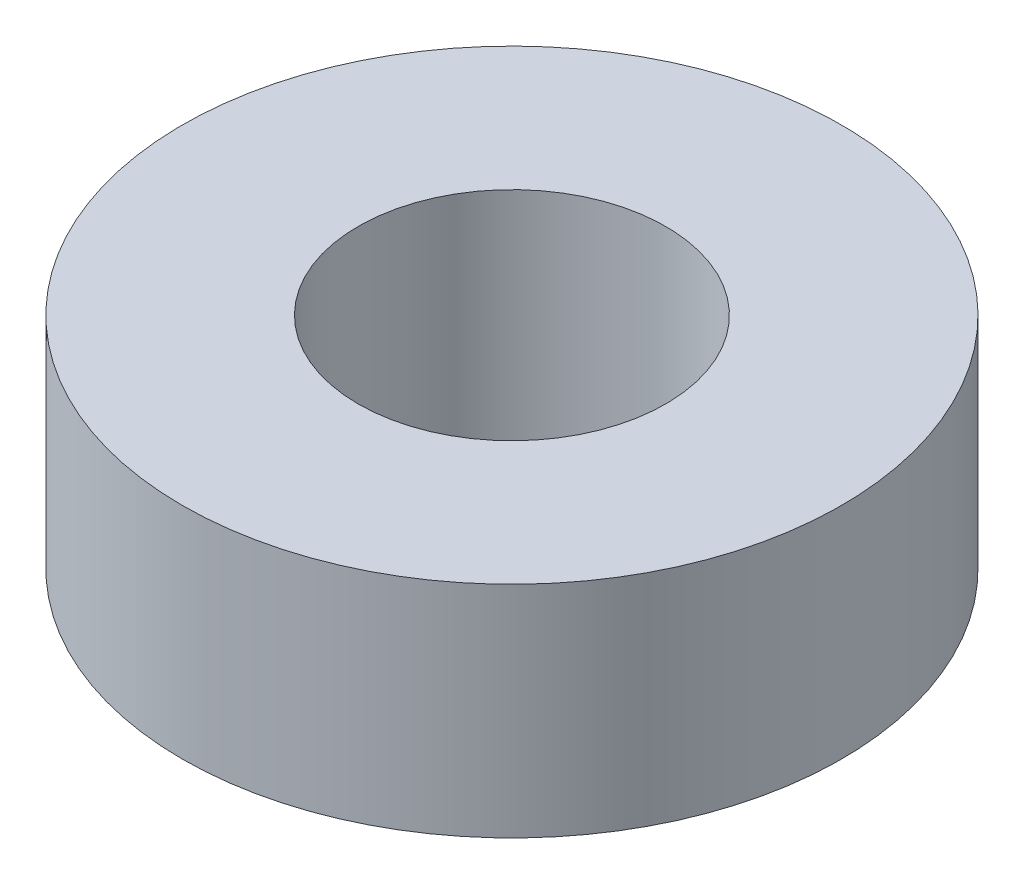
SolidWorks part; units mm, degrees
ref_plane "前视基准面" through (0, 0, 0) normal (0, 0, 1) x (1, 0, 0)
ref_plane "上视基准面" through (0, 0, 0) normal (0, 1, 0) x (1, 0, 0)
ref_plane "右视基准面" through (0, 0, 0) normal (1, 0, 0) x (0, 0, -1)
sketch "草图1" plane through (0, 0, 0) normal (0, 1, 0) x (1, 0, 0)
  circle A0 centre (0, 0) radius 7.5
  circle A1 centre (0, 0) radius 3.5
  dimension "D1" = 15
  dimension "D2" = 7
extrude "凸台-拉伸1" add sketch "草图1" along normal blind 5
